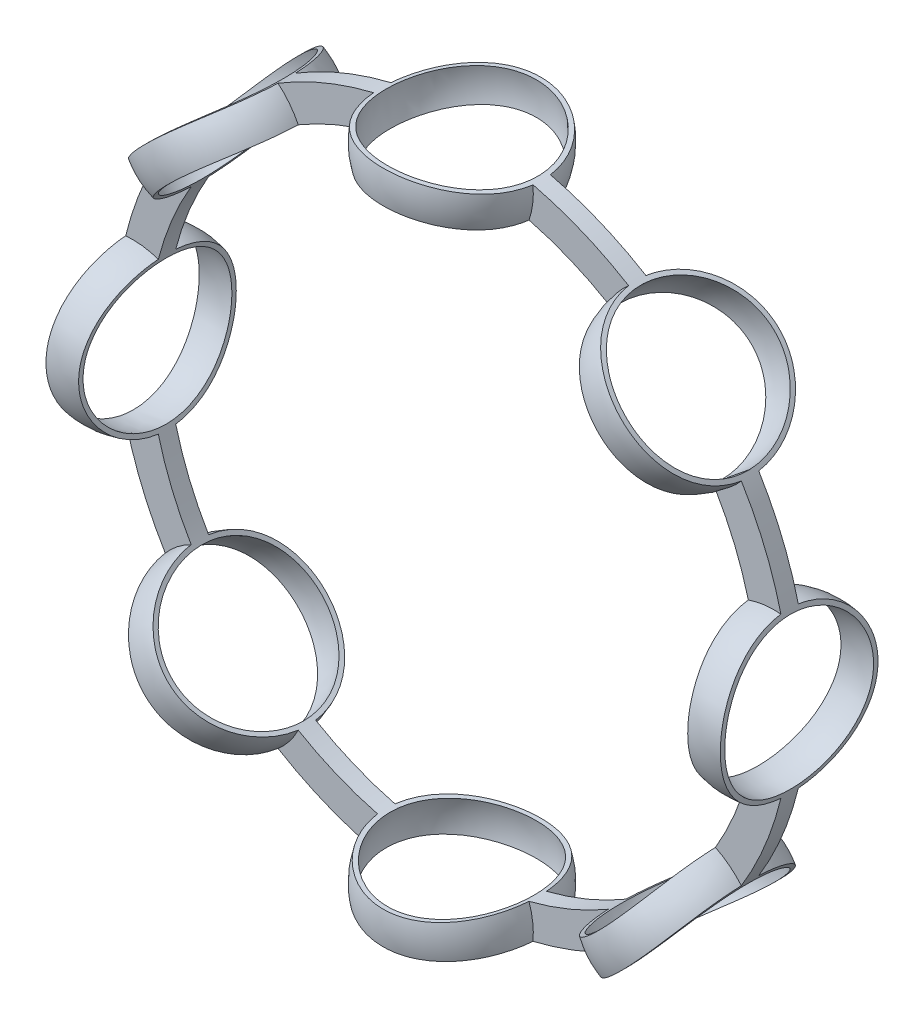
SolidWorks part; units mm, degrees
other "阵列(圆周)2"
material "锻制不锈钢"
ref_plane "前视基准面" through (0, 0, 0) normal (0, 0, 1) x (1, 0, 0)
ref_plane "上视基准面" through (0, 0, 0) normal (0, 1, 0) x (1, 0, 0)
ref_plane "右视基准面" through (0, 0, 0) normal (1, 0, 0) x (0, 0, -1)
sketch "草图1" plane through (0, 0, 0) normal (0, 0, 1) x (1, 0, 0)
  circle A0 centre (0, 0) radius 90
  dimension "D1" = 180
extrude "拉伸1" add sketch "草图1" along normal mid plane 4
sketch "草图4" plane through (0, 0, 0) normal (0, 1, 0) x (1, 0, 0)
  line L0 (73.75, 39.6642) -> (73.75, -39.6642) construction
  line L1 (73.75, 18.5) -> (73.75, -18.5)
  arc A0 (73.75, -18.5) -> (73.75, 18.5) centre (73.75, 0) ccw
  dimension "D1" = 37
  dimension "D2" = 73.75
revolve "旋转1" add sketch "草图4" angle 360 about L0
pattern_circular "阵列(圆周)1" count 8 over 360 about axis through (0, 0, 0) along (0, 0, 1) of "旋转1"
sketch "草图5" plane through (0, 0, 0) normal (0, 0, 1) x (1, 0, 0)
  circle A0 centre (0, 0) radius 77.5
  circle A1 centre (0, 0) radius 70
  dimension "D1" = 155
  dimension "D2" = 140
extrude "切除-拉伸1" cut sketch "草图5" against normal mid plane 70 flip side to cut
sketch "草图7" plane through (0, 0, 0) normal (0, 1, 0) x (1, 0, 0)
  line L0 (73.75, 25.5802) -> (73.75, -26.3487) construction
  line L1 (73.75, 17.5) -> (73.75, -17.5)
  arc A0 (73.75, -17.5) -> (73.75, 17.5) centre (73.75, 0) ccw
  dimension "D1" = 35
  dimension "D2" = 73.75
revolve "切除-旋转1" cut sketch "草图7" angle 360 about L0
pattern_circular "阵列(圆周)2" count 8 over 360 about axis through (0, 0, 0) along (0, 0, 1) of "切除-旋转1"
